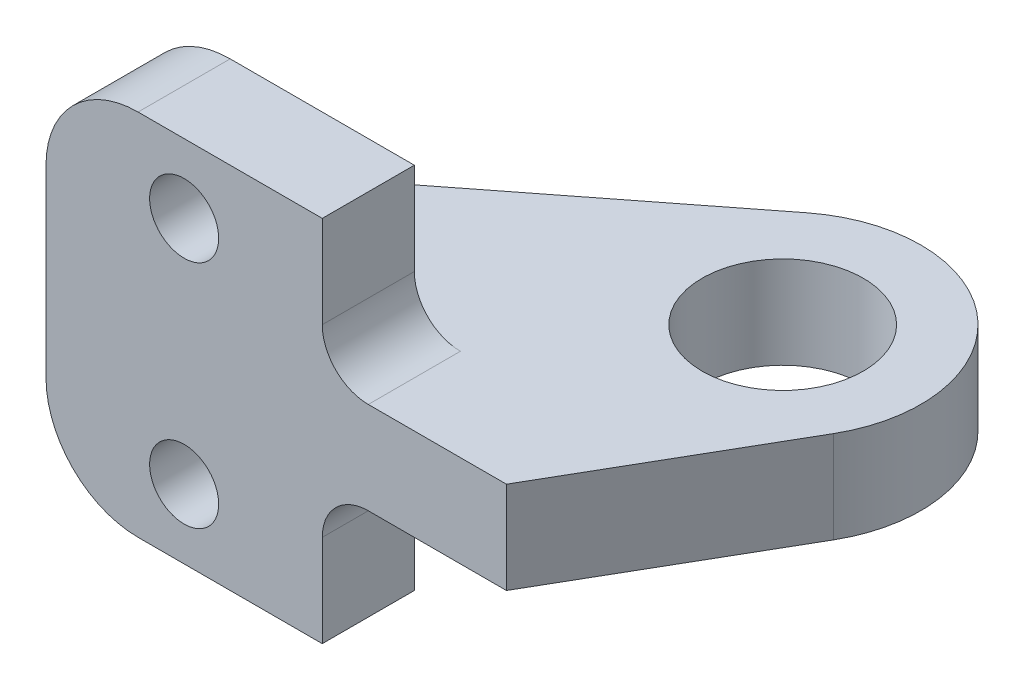
SolidWorks part; units mm, degrees
ref_plane "Front Plane" through (0, 0, 0) normal (0, 0, 1) x (1, 0, 0)
ref_plane "Top Plane" through (0, 0, 0) normal (0, 1, 0) x (1, 0, 0)
ref_plane "Right Plane" through (0, 0, 0) normal (1, 0, 0) x (0, 0, -1)
sketch "Sketch1" plane through (0, 0, 0) normal (0, 1, 0) x (1, 0, 0)
  line L0 (0, 0) -> (127, 0)
  line L1 (0, 0) -> (0, 25.4)
  line L2 (0, 25.4) -> (103.5566, 106.2336)
  line L3 (127, 0) -> (159.9956, 57.15)
  circle A0 centre (127, 76.2) radius 22.225
  circle A1 centre (127, 76.2) radius 38.1
  dimension "D3" = 76.2
  dimension "D4" = 44.45
  dimension "D1" = 25.4
  dimension "D2" = 127
  dimension "D5" = 76.2
  dimension "D6" = 127
extrude "Boss-Extrude1" add sketch "Sketch1" along normal mid plane 25.4 contours A1 L2 L1 L0 L3 | A1 A0
sketch "Sketch2" plane through (0, 12.7, 0) normal (0, 1, 0) x (1, 0, 0)
  line L0 (0, 0) -> (127, 0) construction
  line L1 (0, 25.4) -> (101.6, 25.4)
  line L2 (0, 25.4) -> (0, 0)
  line L3 (0, 0) -> (101.6, 0)
  line L4 (101.6, 25.4) -> (101.6, 0)
  dimension "D1" = 101.6
extrude "Boss-Extrude2" add sketch "Sketch2" along normal blind 38.1
sketch "Sketch3" plane through (0, 0, -25.4) normal (0, 0, -1) x (-1, 0, 0)
  line L0 (-101.6, 50.8) -> (-101.6, 12.7) construction
  line L1 (-101.6, 12.7) -> (0, 12.7) construction
  line L2 (-76.2, 25.4) -> (-76.2, 50.8)
  line L3 (-101.6, 50.8) -> (0, 50.8) construction
  line L4 (-76.2, 50.8) -> (-101.6, 63.5)
  line L5 (-101.6, 63.5) -> (-101.6, 12.7)
  line L6 (-101.6, 12.7) -> (-88.9, 12.7)
  circle A0 centre (-88.9, 25.4) radius 12.7
  line M4 (-101.6, 12.7) -> (0, 12.7)
  line M6 (0, 50.8) -> (-101.6, 50.8)
  line M7 (-101.6, 50.8) -> (-101.6, 12.7)
  dimension "D1" = 25.4
extrude "Cut-Extrude1" cut sketch "Sketch3" against normal through all contours A0 L2 M6 M7 | A0 | A0 L5 M4
sketch "Sketch4" plane through (0, 0, -25.4) normal (0, 0, -1) x (-1, 0, 0)
  line L0 (-76.2, 50.8) -> (0, 50.8) construction
  line L1 (0, 50.8) -> (0, 12.7) construction
  circle A0 centre (-38.1, 31.75) radius 9.525
  dimension "D1" = 19.05
  dimension "D2" = 19.05
  dimension "D3" = 38.1
extrude "Cut-Extrude3" cut sketch "Sketch4" against normal blind 38.1
fillet "Fillet3" radius 25.4 1 edges at (0, 50.8, -12.7)
sketch "Sketch6" plane through (0, -12.7, 0) normal (0, -1, 0) x (1, 0, 0)
  line L5 (0, 0) -> (127, 0) construction
  line L6 (0, -25.4) -> (101.6, -25.4)
  line L7 (0, -25.4) -> (0, 0)
  line L8 (0, 0) -> (101.6, 0)
  line L9 (101.6, -25.4) -> (101.6, 0)
  dimension "D1" = 101.6
extrude "Boss-Extrude3" add sketch "Sketch6" along normal blind 38.1
sketch "Sketch7" plane through (0, 0, -25.4) normal (0, 0, -1) x (-1, 0, 0)
  line L0 (0, -12.7) -> (-101.6, -12.7) construction
  line L1 (-101.6, -50.8) -> (-101.6, -12.7) construction
  line L2 (-76.2, -25.4) -> (-76.2, -50.8)
  line L3 (0, -50.8) -> (-101.6, -50.8) construction
  line L4 (-76.2, -50.8) -> (-101.6, -50.8)
  line L5 (-101.6, -50.8) -> (-101.6, -12.7)
  line L6 (-101.6, -12.7) -> (-88.9, -12.7)
  circle A0 centre (-88.9, -25.4) radius 12.7
  line M4 (0, -12.7) -> (-101.6, -12.7)
  line M5 (-101.6, -12.7) -> (-101.6, -50.8)
  line M6 (-101.6, -50.8) -> (0, -50.8)
  dimension "D1" = 25.4
extrude "Cut-Extrude4" cut sketch "Sketch7" against normal through all contours A0 L5 L2 M6 | A0 | A0 M4 M5
sketch "Sketch8" plane through (0, 0, -25.4) normal (0, 0, -1) x (-1, 0, 0)
  line L0 (0, -50.8) -> (-76.2, -50.8) construction
  line L1 (0, -50.8) -> (0, -12.7) construction
  circle A0 centre (-38.1, -31.75) radius 9.525
  dimension "D1" = 19.05
  dimension "D2" = 19.05
  dimension "D3" = 38.1
extrude "Cut-Extrude5" cut sketch "Sketch8" against normal through all
fillet "Fillet4" radius 25.4 1 edges at (0, -50.8, -12.7)
